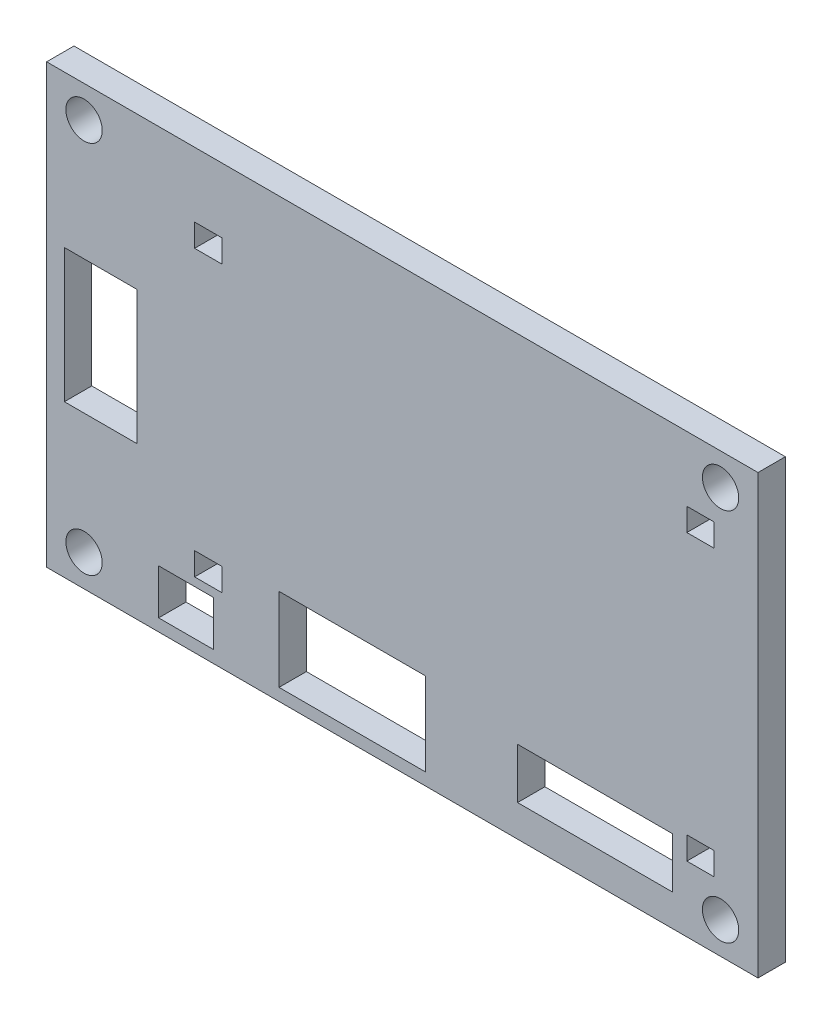
SolidWorks part; units mm, degrees
material "Beech"
ref_plane "Front Plane" through (0, 0, 0) normal (0, 0, 1) x (1, 0, 0)
ref_plane "Top Plane" through (0, 0, 0) normal (0, 1, 0) x (1, 0, 0)
ref_plane "Right Plane" through (0, 0, 0) normal (1, 0, 0) x (0, 0, -1)
sketch "Sketch1" plane through (0, 0, 0) normal (0, 0, 1) x (1, 0, 0)
  line L0 (-20.6375, 0) -> (20.6375, 0)
  line L44 (0, 14.605) -> (0, 24.13) construction
  line L46 (-20.6375, 0) -> (-20.6375, 25.4)
  line L47 (-20.6375, 25.4) -> (20.6375, 25.4)
  line L48 (20.6375, 0) -> (20.6375, 25.4)
  line L49 (-20.6375, 12.7) -> (20.6375, 12.7) construction
  circle A2 centre (-18.4658, 23.5585) radius 1.0541
  circle A3 centre (-18.4658, 1.8415) radius 1.0541
  circle A4 centre (18.4658, 1.8415) radius 1.0541
  circle A5 centre (18.4658, 23.5585) radius 1.0541
  point P0 (0, 0)
  point P56 (0, 12.7)
  point P60 (0, 25.4)
  dimension "D14" = 12.7
  dimension "D4" = 2.1082
  dimension "D3" = 25.4
  dimension "D12" = 41.275
  dimension "D5" = 2.1717
  dimension "D6" = 1.8415
extrude "Boss-Extrude1" add sketch "Sketch1" along normal blind 1.5875
fillet "Fillet7" [suppressed] radius 15.24
sketch "Sketch2" plane through (0, 0, 1.5875) normal (0, 0, 1) x (1, 0, 0)
  line L0 (16.51, 20.32) -> (16.51, 21.6408) construction
  line L1 (16.51, 21.6408) -> (18.0975, 21.6408) construction
  line L2 (18.0975, 21.6408) -> (18.0975, 20.32) construction
  line L3 (18.0975, 20.32) -> (16.51, 20.32) construction
  line L4 (6.6858, 1.8395) -> (15.6858, 1.8395)
  line L5 (6.6858, 4.7695) -> (6.6858, 1.8395)
  line L6 (15.6858, 4.7695) -> (6.6858, 4.7695)
  line L7 (15.6858, 1.8395) -> (15.6858, 4.7695)
  line L8 (6.6858, 1.8395) -> (15.6858, 1.8395)
  line L9 (6.6858, 4.7695) -> (6.6858, 1.8395)
  line L10 (15.6858, 4.7695) -> (6.6858, 4.7695)
  line L11 (15.6858, 1.8395) -> (15.6858, 4.7695)
  line L12 (1.3552, 5.5335) -> (-7.1538, 5.5335)
  line L13 (1.3552, 0.7075) -> (1.3552, 5.5335)
  line L14 (-7.1538, 0.7075) -> (1.3552, 0.7075)
  line L15 (-7.1538, 5.5335) -> (-7.1538, 0.7075)
  line L16 (1.3552, 5.5335) -> (-7.1538, 5.5335)
  line L17 (1.3552, 0.7075) -> (1.3552, 5.5335)
  line L18 (-7.1538, 0.7075) -> (1.3552, 0.7075)
  line L19 (-7.1538, 5.5335) -> (-7.1538, 0.7075)
  line L20 (-10.9638, 3.3237) -> (-14.1388, 3.3237)
  line L21 (-10.9638, 0.7075) -> (-10.9638, 3.3237)
  line L22 (-14.1388, 0.7075) -> (-10.9638, 0.7075)
  line L23 (-14.1388, 3.3237) -> (-14.1388, 0.7075)
  line L24 (-10.9638, 3.3237) -> (-14.1388, 3.3237)
  line L25 (-10.9638, 0.7075) -> (-10.9638, 3.3237)
  line L26 (-14.1388, 0.7075) -> (-10.9638, 0.7075)
  line L27 (-14.1388, 3.3237) -> (-14.1388, 0.7075)
  line L28 (-19.6078, 8.834) -> (-15.3878, 8.834)
  line L29 (-19.6078, 16.584) -> (-19.6078, 8.834)
  line L30 (-15.3878, 16.584) -> (-19.6078, 16.584)
  line L31 (-15.3878, 8.834) -> (-15.3878, 16.584)
  line L32 (-19.6078, 8.834) -> (-15.3878, 8.834)
  line L33 (-19.6078, 16.584) -> (-19.6078, 8.834)
  line L34 (-15.3878, 16.584) -> (-19.6078, 16.584)
  line L35 (-15.3878, 8.834) -> (-15.3878, 16.584)
  line L36 (16.51, 3.81) -> (16.51, 5.1308) construction
  line L37 (16.51, 5.1308) -> (18.0975, 5.1308) construction
  line L38 (18.0975, 5.1308) -> (18.0975, 3.81) construction
  line L39 (18.0975, 3.81) -> (16.51, 3.81) construction
  line L40 (-12.0523, 3.81) -> (-12.0523, 5.1308) construction
  line L41 (-12.0523, 5.1308) -> (-10.4648, 5.1308) construction
  line L42 (-10.4648, 5.1308) -> (-10.4648, 3.81) construction
  line L43 (-10.4648, 3.81) -> (-12.0523, 3.81) construction
  line L44 (-12.0523, 20.32) -> (-12.0523, 21.6408) construction
  line L45 (-12.0523, 21.6408) -> (-10.4648, 21.6408) construction
  line L46 (-10.4648, 21.6408) -> (-10.4648, 20.32) construction
  line L47 (-10.4648, 20.32) -> (-12.0523, 20.32) construction
  line L48 (16.51, 20.32) -> (16.51, 21.6408)
  line L49 (16.51, 21.6408) -> (18.0975, 21.6408)
  line L50 (18.0975, 21.6408) -> (18.0975, 20.32)
  line L51 (18.0975, 20.32) -> (16.51, 20.32)
  line L52 (16.51, 3.81) -> (16.51, 5.1308)
  line L53 (16.51, 5.1308) -> (18.0975, 5.1308)
  line L54 (18.0975, 5.1308) -> (18.0975, 3.81)
  line L55 (18.0975, 3.81) -> (16.51, 3.81)
  line L56 (-12.0523, 3.81) -> (-12.0523, 5.1308)
  line L57 (-12.0523, 5.1308) -> (-10.4648, 5.1308)
  line L58 (-10.4648, 5.1308) -> (-10.4648, 3.81)
  line L59 (-10.4648, 3.81) -> (-12.0523, 3.81)
  line L60 (-12.0523, 20.32) -> (-12.0523, 21.6408)
  line L61 (-12.0523, 21.6408) -> (-10.4648, 21.6408)
  line L62 (-10.4648, 21.6408) -> (-10.4648, 20.32)
  line L63 (-10.4648, 20.32) -> (-12.0523, 20.32)
  dimension "D1" = 0
  dimension "D2" = 0
  dimension "D3" = 0
  dimension "D4" = 0
extrude "Cut-Extrude1" cut sketch "Sketch2" against normal up to surface (1.5875 mm away) up to face at (-17.4117, 1.8415, 0)
